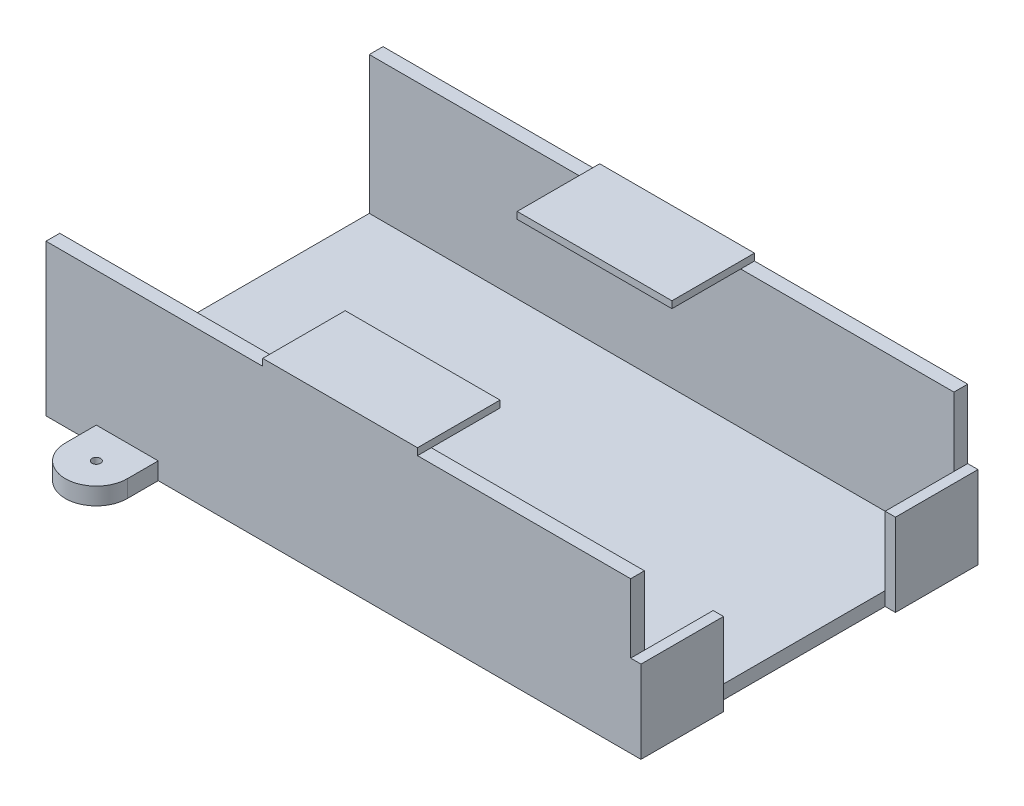
SolidWorks part; units mm, degrees
ref_plane "Front Plane" through (0, 0, 0) normal (0, 0, 1) x (1, 0, 0)
ref_plane "Top Plane" through (0, 0, 0) normal (0, 1, 0) x (1, 0, 0)
ref_plane "Right Plane" through (0, 0, 0) normal (1, 0, 0) x (0, 0, -1)
sketch "Sketch1" plane through (0, 0, 0) normal (0, 1, 0) x (1, 0, 0)
  line L1 (-215.9, -57.15) -> (0, -57.15)
  line L2 (-215.9, -57.15) -> (-215.9, 57.15)
  line L3 (-215.9, 57.15) -> (0, 57.15)
  line L4 (0, -57.15) -> (0, 57.15)
  dimension "D1" = 114.3
  dimension "D2" = 215.9
extrude "Boss-Extrude1" add sketch "Sketch1" along normal blind 5.08
sketch "Sketch2" plane through (0, 0, 57.15) normal (0, 0, 1) x (1, 0, 0)
  line L1 (-215.9, 0) -> (0, 0)
  line L2 (-215.9, 0) -> (-215.9, 55.88)
  line L3 (-215.9, 55.88) -> (0, 55.88)
  line L4 (0, 0) -> (0, 55.88)
  dimension "D1" = 215.9
  dimension "D2" = 55.88
extrude "Boss-Extrude2" add sketch "Sketch2" along normal blind 5.08
mirror "Mirror1" about plane through (0, 0, 0) normal (0, 0, 1) of "Boss-Extrude2"
sketch "Sketch4" plane through (0, 0, 0) normal (1, 0, 0) x (0, 0, -1)
  line L1 (-62.23, 30.48) -> (-31.75, 30.48)
  line L2 (-62.23, 30.48) -> (-62.23, 0)
  line L3 (-62.23, 0) -> (-31.75, 0)
  line L4 (-31.75, 30.48) -> (-31.75, 0)
  line L6 (-62.23, 0) -> (-62.23, 55.88) construction
  line L10 (-62.23, 0) -> (62.23, 0) construction
  line L11 (0, 30.734) -> (0, -30.734) construction
  line L12 (62.23, 0) -> (31.75, 0)
  line L13 (31.75, 30.48) -> (31.75, 0)
  line L14 (62.23, 30.48) -> (31.75, 30.48)
  line L15 (62.23, 30.48) -> (62.23, 0)
  dimension "D1" = 30.48
  dimension "D2" = 30.48
extrude "Boss-Extrude3" add sketch "Sketch4" along normal blind 3.81
ref_plane "Plane1" through (0, 55.88, 0) normal (0, 1, 0) x (1, 0, 0)
sketch "Sketch5" plane through (0, 55.88, 0) normal (0, 1, 0) x (1, 0, 0)
  line L0 (0, 62.23) -> (-215.9, 62.23) construction
  line L1 (-135.8842, 62.23) -> (-78.7342, 62.23)
  line L2 (-135.8842, 62.23) -> (-135.8842, 31.75)
  line L3 (-135.8842, 31.75) -> (-78.7342, 31.75)
  line L4 (-78.7342, 62.23) -> (-78.7342, 31.75)
  line L5 (0, -62.23) -> (-215.9, -62.23) construction
  line L6 (-135.8842, -62.23) -> (-78.7146, -62.23)
  line L7 (-135.8842, -62.23) -> (-135.8842, -31.75)
  line L8 (-135.8842, -31.75) -> (-78.7146, -31.75)
  line L9 (-78.7146, -62.23) -> (-78.7146, -31.75)
  line L10 (3.81, -31.75) -> (0, -31.75) construction
  line L11 (3.81, 31.75) -> (0, 31.75) construction
  dimension "D1" = 57.15
  dimension "D2" = 78.7342
  dimension "D3" = 78.7146
extrude "Boss-Extrude4" add sketch "Sketch5" along normal blind 2.54
sketch "Sketch12" plane through (0, 0, 0) normal (0, 1, 0) x (1, 0, 0)
  line L0 (-62.23, 62.23) -> (-62.23, 73.66)
  line L1 (0, 62.23) -> (-78.7342, 62.23) construction
  line L2 (-39.37, 62.23) -> (-39.37, 73.66)
  line L3 (-62.23, 62.23) -> (-39.37, 62.23)
  arc A0 (-62.23, 73.66) -> (-39.37, 73.66) centre (-50.8, 73.66) cw
  dimension "D1" = 22.86
  dimension "D3" = 43.18
  dimension "D2" = 11.43
extrude "Boss-Extrude6" add sketch "Sketch12" along normal blind 15.875 contours L2 A0 L0 L3
sketch "Sketch14" plane through (0, 15.875, 0) normal (0, 1, 0) x (1, 0, 0)
  line L0 (-50.8, 62.23) -> (-50.8, 85.09) construction
  line L1 (-62.23, 62.23) -> (-39.37, 62.23) construction
  line L2 (-62.23, 73.66) -> (-39.37, 73.66) construction
  arc A0 (-39.37, 73.66) -> (-62.23, 73.66) centre (-50.8, 73.66) ccw construction
  circle A1 centre (-50.8, 73.66) radius 1.5875
  dimension "D1" = 3.175
extrude "Cut-Extrude1" cut sketch "Sketch14" against normal through all
sketch "Sketch19" plane through (0, 0, 0) normal (0, -1, 0) x (1, 0, 0)
  line L0 (-62.23, -62.23) -> (-62.23, -73.66)
  line L1 (-62.23, -62.23) -> (-39.37, -62.23)
  line L2 (-39.37, -62.23) -> (-39.37, -73.66)
  arc A0 (-62.23, -73.66) -> (-39.37, -73.66) centre (-50.8, -73.66) ccw
ref_plane "Plane3" through (-114.3, 0, 0) normal (-1, 0, 0) x (0, 0, 1)
sketch "Sketch20" plane through (0, 0, 0) normal (0, 1, 0) x (1, 0, 0)
  line L0 (-197.3179, 62.23) -> (-197.3179, 73.66)
  line L1 (-135.8842, 62.23) -> (-215.9, 62.23) construction
  line L2 (-174.4579, 62.23) -> (-174.4579, 73.66)
  line L3 (-197.3179, 62.23) -> (-174.4579, 62.23)
  arc A0 (-197.3179, 73.66) -> (-174.4579, 73.66) centre (-185.8879, 73.66) cw
  dimension "D1" = 11.43
  dimension "D3" = 185.8879
  dimension "D2" = 11.43
extrude "Boss-Extrude7" add sketch "Sketch20" along normal blind 15.875
sketch "Sketch21" plane through (0, 15.875, 0) normal (0, 1, 0) x (1, 0, 0)
  line L0 (-197.3179, 73.66) -> (-174.4579, 73.66) construction
  line L1 (-185.8879, 85.09) -> (-185.8879, 62.23) construction
  line L2 (-197.3179, 62.23) -> (-174.4579, 62.23) construction
  arc A0 (-174.4579, 73.66) -> (-197.3179, 73.66) centre (-185.8879, 73.66) ccw construction
  circle A1 centre (-185.8879, 73.66) radius 1.5875
  dimension "D1" = 3.175
extrude "Cut-Extrude6" cut sketch "Sketch21" against normal through all
mirror "Mirror4" about plane through (0, 0, 0) normal (0, 0, 1) of "Boss-Extrude7"
mirror "Mirror5" about plane through (0, 0, 0) normal (0, 0, 1) of "Cut-Extrude6"
sketch "Sketch25" plane through (0, 15.875, 0) normal (0, 1, 0) x (1, 0, 0)
  line L0 (-197.3179, -62.23) -> (-197.3179, -73.66)
  line L1 (-174.4579, -62.23) -> (-174.4579, -73.66)
  line L2 (-197.3179, -62.23) -> (-174.4579, -62.23)
  arc A0 (-197.3179, -73.66) -> (-174.4579, -73.66) centre (-185.8879, -73.66) ccw
extrude "Cut-Extrude10" cut sketch "Sketch25" against normal blind 9.525
sketch "Sketch26" plane through (0, 15.875, 0) normal (0, 1, 0) x (1, 0, 0)
  line L0 (-62.23, 62.23) -> (-39.37, 62.23)
  line L1 (-39.37, 62.23) -> (-39.37, 73.66)
  line L2 (-62.23, 73.66) -> (-62.23, 62.23)
  arc A0 (-62.23, 73.66) -> (-39.37, 73.66) centre (-50.8, 73.66) cw
  arc A1 (-39.37, 73.66) -> (-62.23, 73.66) centre (-50.8, 73.66) ccw construction
  point P10 (-39.3703, 73.7429)
extrude "Cut-Extrude11" cut sketch "Sketch26" against normal blind 8.89
sketch "Sketch27" plane through (0, 15.875, 0) normal (0, 1, 0) x (1, 0, 0)
  line L0 (-197.3179, 62.23) -> (-174.4579, 62.23)
  line L1 (-197.3179, 73.66) -> (-197.3179, 62.23)
  line L2 (-174.4579, 73.66) -> (-174.4579, 62.23)
  arc A0 (-197.3179, 73.66) -> (-174.4579, 73.66) centre (-185.8879, 73.66) cw
extrude "Cut-Extrude12" cut sketch "Sketch27" against normal blind 8.89
